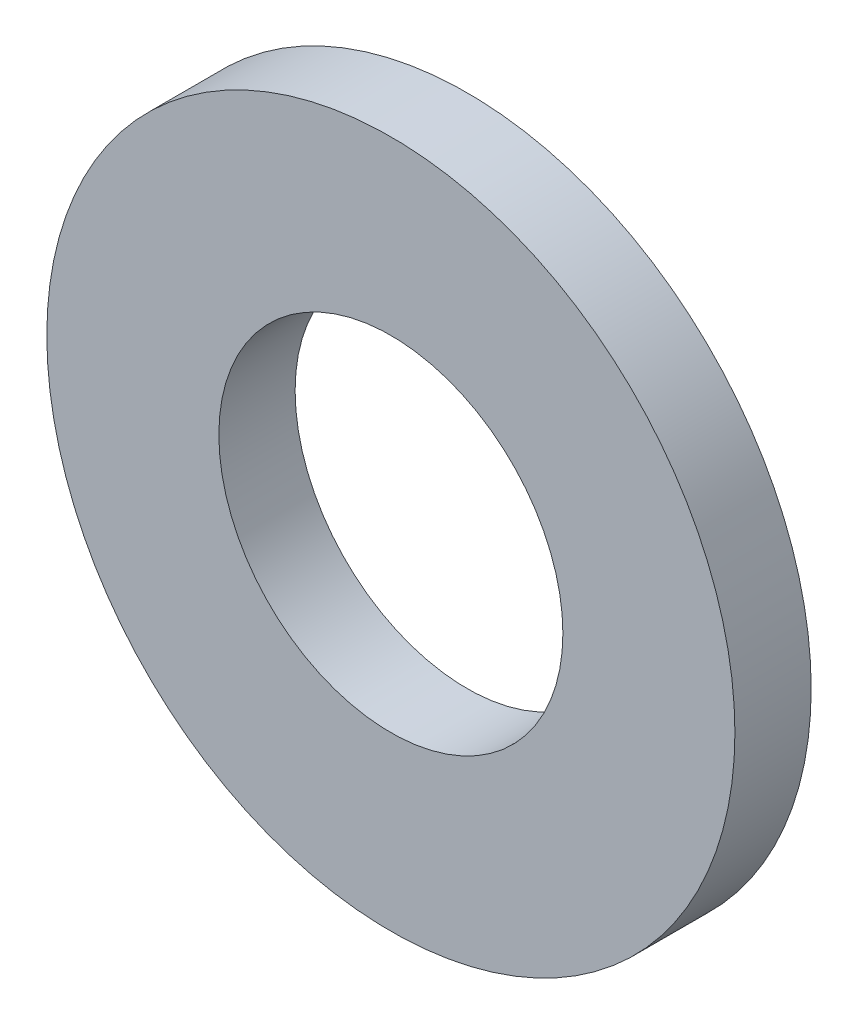
SolidWorks part; units mm, degrees
material "AISI Type 316L stainless steel"
ref_plane "X-Y Plane" through (0, 0, 0) normal (0, 0, 1) x (1, 0, 0)
ref_plane "Z-X Plane" through (0, 0, 0) normal (0, 1, 0) x (1, 0, 0)
ref_plane "Y-Z Plane" through (0, 0, 0) normal (1, 0, 0) x (0, 0, -1)
sketch "Sketch1" plane through (0, 0, 0) normal (1, 0, 0) x (0, 0, -1)
  line L0 (0, 0) -> (3.5208, 0) construction
  line L1 (0, 2.5781) -> (1.143, 2.5781)
  line L2 (0, 2.5781) -> (0, 5.1562)
  line L3 (0, 5.1562) -> (1.143, 5.1562)
  line L4 (1.143, 2.5781) -> (1.143, 5.1562)
  dimension "D1" = 5.1562
  dimension "D2" = 10.3124
  dimension "D3" = 1.143
revolve "Revolve1" add sketch "Sketch1" angle 360 about L0
